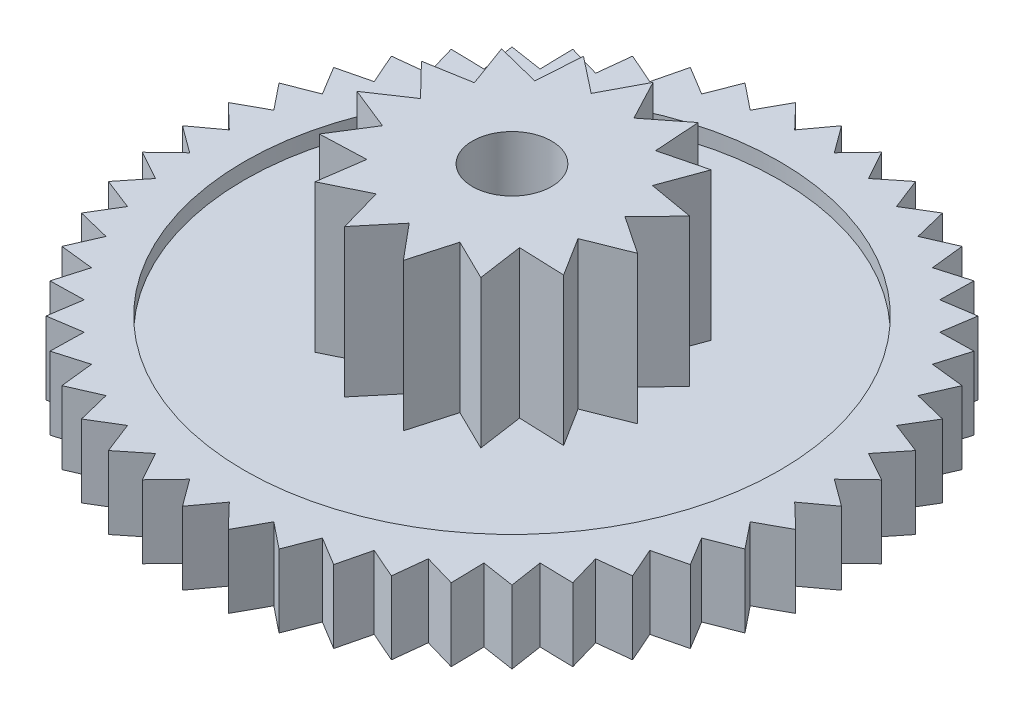
SolidWorks part; units mm, degrees
ref_plane "Front Plane" through (0, 0, 0) normal (0, 0, 1) x (1, 0, 0)
ref_plane "Top Plane" through (0, 0, 0) normal (0, 1, 0) x (1, 0, 0)
ref_plane "Right Plane" through (0, 0, 0) normal (1, 0, 0) x (0, 0, -1)
sketch "Sketch1" plane through (0, 0, 0) normal (0, 0, 1) x (1, 0, 0)
  line L0 (0, 3.88) -> (0, 0)
  line L1 (0, -55) -> (0, 55) construction
  line L2 (0, 0) -> (1.67, 0)
  line L3 (55, 0) -> (-55, 0) construction
  line L4 (6.25, 0) -> (6.25, 1.38)
  line L5 (6.25, 1.38) -> (5.075, 1.38)
  line L6 (2.675, 1.08) -> (2.675, 3.88)
  line L7 (2.675, 3.88) -> (0, 3.88)
  line L8 (5.075, 1.38) -> (5.075, 1.08)
  line L9 (5.075, 1.08) -> (2.675, 1.08)
  line L10 (5.075, 0) -> (5.075, 0.3)
  line L11 (5.075, 0.3) -> (1.67, 0.3)
  line L12 (1.67, 0.3) -> (1.67, 0)
  line L13 (5.075, 0) -> (6.25, 0)
  dimension "D1" = 2.675
  dimension "D2" = 6.25
  dimension "D3" = 5.075
  dimension "D4" = 1.38
  dimension "D5" = 0.3
  dimension "D6" = 1.67
  dimension "D7" = 3.88
revolve "Revolve1" add sketch "Sketch1" angle 360 about L0
sketch "Sketch2" plane through (0, 1.38, 0) normal (0, 1, 0) x (1, 0, 0)
  line L0 (-0.3761, 5.7377) -> (0, 6.25)
  line L1 (0, -2.134) -> (0, 2.134) construction
  line L2 (0, 6.25) -> (0.3761, 5.7377)
  line L3 (-0.3761, 5.7377) -> (0, 0) construction
  line L4 (0, 0) -> (0.3761, 5.7377) construction
  line L5 (0.3761, 5.7377) -> (0.8158, 6.1965)
  line L6 (0.8158, 6.1965) -> (1.1218, 5.6395)
  line L7 (1.1218, 5.6395) -> (1.6176, 6.037)
  line L8 (1.6176, 6.037) -> (1.8483, 5.4448)
  line L9 (1.8483, 5.4448) -> (2.3918, 5.7742)
  line L10 (2.3918, 5.7742) -> (2.5432, 5.157)
  line L11 (2.5432, 5.157) -> (3.125, 5.4127)
  line L12 (3.125, 5.4127) -> (3.1945, 4.781)
  line L13 (3.1945, 4.781) -> (3.8048, 4.9585)
  line L14 (3.8048, 4.9585) -> (3.7912, 4.3231)
  line L15 (3.7912, 4.3231) -> (4.4194, 4.4194)
  line L16 (4.4194, 4.4194) -> (4.3231, 3.7912)
  line L17 (4.3231, 3.7912) -> (4.9585, 3.8048)
  line L18 (4.9585, 3.8048) -> (4.781, 3.1945)
  line L19 (4.781, 3.1945) -> (5.4127, 3.125)
  line L20 (5.4127, 3.125) -> (5.157, 2.5432)
  line L21 (5.157, 2.5432) -> (5.7742, 2.3918)
  line L22 (5.7742, 2.3918) -> (5.4448, 1.8483)
  line L23 (5.4448, 1.8483) -> (6.037, 1.6176)
  line L24 (6.037, 1.6176) -> (5.6395, 1.1218)
  line L25 (5.6395, 1.1218) -> (6.1965, 0.8158)
  line L26 (6.1965, 0.8158) -> (5.7377, 0.3761)
  line L27 (5.7377, 0.3761) -> (6.25, 0)
  line L28 (6.25, 0) -> (5.7377, -0.3761)
  line L29 (5.7377, -0.3761) -> (6.1965, -0.8158)
  line L30 (6.1965, -0.8158) -> (5.6395, -1.1218)
  line L31 (5.6395, -1.1218) -> (6.037, -1.6176)
  line L32 (6.037, -1.6176) -> (5.4448, -1.8483)
  line L33 (5.4448, -1.8483) -> (5.7742, -2.3918)
  line L34 (5.7742, -2.3918) -> (5.157, -2.5432)
  line L35 (5.157, -2.5432) -> (5.4127, -3.125)
  line L36 (5.4127, -3.125) -> (4.781, -3.1945)
  line L37 (4.781, -3.1945) -> (4.9585, -3.8048)
  line L38 (4.9585, -3.8048) -> (4.3231, -3.7912)
  line L39 (4.3231, -3.7912) -> (4.4194, -4.4194)
  line L40 (4.4194, -4.4194) -> (3.7912, -4.3231)
  line L41 (3.7912, -4.3231) -> (3.8048, -4.9585)
  line L42 (3.8048, -4.9585) -> (3.1945, -4.781)
  line L43 (3.1945, -4.781) -> (3.125, -5.4127)
  line L44 (3.125, -5.4127) -> (2.5432, -5.157)
  line L45 (2.5432, -5.157) -> (2.3918, -5.7742)
  line L46 (2.3918, -5.7742) -> (1.8483, -5.4448)
  line L47 (1.8483, -5.4448) -> (1.6176, -6.037)
  line L48 (1.6176, -6.037) -> (1.1218, -5.6395)
  line L49 (1.1218, -5.6395) -> (0.8158, -6.1965)
  line L50 (0.8158, -6.1965) -> (0.3761, -5.7377)
  line L51 (0.3761, -5.7377) -> (0, -6.25)
  line L52 (0, -6.25) -> (-0.3761, -5.7377)
  line L53 (-0.3761, -5.7377) -> (-0.8158, -6.1965)
  line L54 (-0.8158, -6.1965) -> (-1.1218, -5.6395)
  line L55 (-1.1218, -5.6395) -> (-1.6176, -6.037)
  line L56 (-1.6176, -6.037) -> (-1.8483, -5.4448)
  line L57 (-1.8483, -5.4448) -> (-2.3918, -5.7742)
  line L58 (-2.3918, -5.7742) -> (-2.5432, -5.157)
  line L59 (-2.5432, -5.157) -> (-3.125, -5.4127)
  line L60 (-3.125, -5.4127) -> (-3.1945, -4.781)
  line L61 (-3.1945, -4.781) -> (-3.8048, -4.9585)
  line L62 (-3.8048, -4.9585) -> (-3.7912, -4.3231)
  line L63 (-3.7912, -4.3231) -> (-4.4194, -4.4194)
  line L64 (-4.4194, -4.4194) -> (-4.3231, -3.7912)
  line L65 (-4.3231, -3.7912) -> (-4.9585, -3.8048)
  line L66 (-4.9585, -3.8048) -> (-4.781, -3.1945)
  line L67 (-4.781, -3.1945) -> (-5.4127, -3.125)
  line L68 (-5.4127, -3.125) -> (-5.157, -2.5432)
  line L69 (-5.157, -2.5432) -> (-5.7742, -2.3918)
  line L70 (-5.7742, -2.3918) -> (-5.4448, -1.8483)
  line L71 (-5.4448, -1.8483) -> (-6.037, -1.6176)
  line L72 (-6.037, -1.6176) -> (-5.6395, -1.1218)
  line L73 (-5.6395, -1.1218) -> (-6.1965, -0.8158)
  line L74 (-6.1965, -0.8158) -> (-5.7377, -0.3761)
  line L75 (-5.7377, -0.3761) -> (-6.25, 0)
  line L76 (-6.25, 0) -> (-5.7377, 0.3761)
  line L77 (-5.7377, 0.3761) -> (-6.1965, 0.8158)
  line L78 (-6.1965, 0.8158) -> (-5.6395, 1.1218)
  line L79 (-5.6395, 1.1218) -> (-6.037, 1.6176)
  line L80 (-6.037, 1.6176) -> (-5.4448, 1.8483)
  line L81 (-5.4448, 1.8483) -> (-5.7742, 2.3918)
  line L82 (-5.7742, 2.3918) -> (-5.157, 2.5432)
  line L83 (-5.157, 2.5432) -> (-5.4127, 3.125)
  line L84 (-5.4127, 3.125) -> (-4.781, 3.1945)
  line L85 (-4.781, 3.1945) -> (-4.9585, 3.8048)
  line L86 (-4.9585, 3.8048) -> (-4.3231, 3.7912)
  line L87 (-4.3231, 3.7912) -> (-4.4194, 4.4194)
  line L88 (-4.4194, 4.4194) -> (-3.7912, 4.3231)
  line L89 (-3.7912, 4.3231) -> (-3.8048, 4.9585)
  line L90 (-3.8048, 4.9585) -> (-3.1945, 4.781)
  line L91 (-3.1945, 4.781) -> (-3.125, 5.4127)
  line L92 (-3.125, 5.4127) -> (-2.5432, 5.157)
  line L93 (-2.5432, 5.157) -> (-2.3918, 5.7742)
  line L94 (-2.3918, 5.7742) -> (-1.8483, 5.4448)
  line L95 (-1.8483, 5.4448) -> (-1.6176, 6.037)
  line L96 (-1.6176, 6.037) -> (-1.1218, 5.6395)
  line L97 (-1.1218, 5.6395) -> (-0.8158, 6.1965)
  line L98 (-0.8158, 6.1965) -> (-0.3761, 5.7377)
  circle A0 centre (0, 0) radius 6.25 construction
  circle A1 centre (0, 0) radius 5.75 construction
  circle A4 centre (0, 0) radius 7.25
  circle A5 centre (0, 0) radius 7.25
  point P155 (0, 0)
  dimension "D2" = 0.5
  dimension "D1" = 7.5
  dimension "D4" = 1
  dimension "D3" = 48
extrude "Cut-Extrude1" cut sketch "Sketch2" against normal through all
sketch "Sketch3" plane through (0, 3.88, 0) normal (0, 1, 0) x (1, 0, 0)
  line L0 (0, 2.675) -> (-0.4054, 1.9074)
  line L1 (0, -2.134) -> (0, 2.134) construction
  line L2 (-0.4054, 1.9074) -> (0, 0) construction
  line L3 (0, 0) -> (0.4054, 1.9074) construction
  line L4 (0.4054, 1.9074) -> (0, 2.675)
  line L5 (1.1462, 1.5776) -> (1.088, 2.4437)
  line L6 (1.088, 2.4437) -> (0.4054, 1.9074)
  line L7 (1.6887, 0.975) -> (1.9879, 1.7899)
  line L8 (1.9879, 1.7899) -> (1.1462, 1.5776)
  line L9 (1.9393, 0.2038) -> (2.5441, 0.8266)
  line L10 (2.5441, 0.8266) -> (1.6887, 0.975)
  line L11 (1.8546, -0.6026) -> (2.6603, -0.2796)
  line L12 (2.6603, -0.2796) -> (1.9393, 0.2038)
  line L13 (1.4491, -1.3048) -> (2.3166, -1.3375)
  line L14 (2.3166, -1.3375) -> (1.8546, -0.6026)
  line L15 (0.7931, -1.7814) -> (1.5723, -2.1641)
  line L16 (1.5723, -2.1641) -> (1.4491, -1.3048)
  line L17 (0, -1.95) -> (0.5562, -2.6165)
  line L18 (0.5562, -2.6165) -> (0.7931, -1.7814)
  line L19 (-0.7931, -1.7814) -> (-0.5562, -2.6165)
  line L20 (-0.5562, -2.6165) -> (0, -1.95)
  line L21 (-1.4491, -1.3048) -> (-1.5723, -2.1641)
  line L22 (-1.5723, -2.1641) -> (-0.7931, -1.7814)
  line L23 (-1.8546, -0.6026) -> (-2.3166, -1.3375)
  line L24 (-2.3166, -1.3375) -> (-1.4491, -1.3048)
  line L25 (-1.9393, 0.2038) -> (-2.6603, -0.2796)
  line L26 (-2.6603, -0.2796) -> (-1.8546, -0.6026)
  line L27 (-1.6887, 0.975) -> (-2.5441, 0.8266)
  line L28 (-2.5441, 0.8266) -> (-1.9393, 0.2038)
  line L29 (-1.1462, 1.5776) -> (-1.9879, 1.7899)
  line L30 (-1.9879, 1.7899) -> (-1.6887, 0.975)
  line L31 (-0.4054, 1.9074) -> (-1.088, 2.4437)
  line L32 (-1.088, 2.4437) -> (-1.1462, 1.5776)
  circle A0 centre (0, 0) radius 1.95 construction
  circle A1 centre (0, 0) radius 2.675 construction
  circle A4 centre (0, 0) radius 3.175
  circle A5 centre (0, 0) radius 3.175
  point P56 (0, 0)
  dimension "D2" = 3.9
  dimension "D1" = 24
  dimension "D4" = 0.5
  dimension "D3" = 15
extrude "Cut-Extrude3" cut sketch "Sketch3" against normal up to surface (2.8 mm away) up to face at (0, 1.08, 2.675)
sketch "Sketch4" plane through (0, 3.88, 0) normal (0, 1, 0) x (1, 0, 0)
  circle A0 centre (0, 0) radius 0.75
  dimension "D1" = 1.5
extrude "Cut-Extrude4" cut sketch "Sketch4" against normal through all
